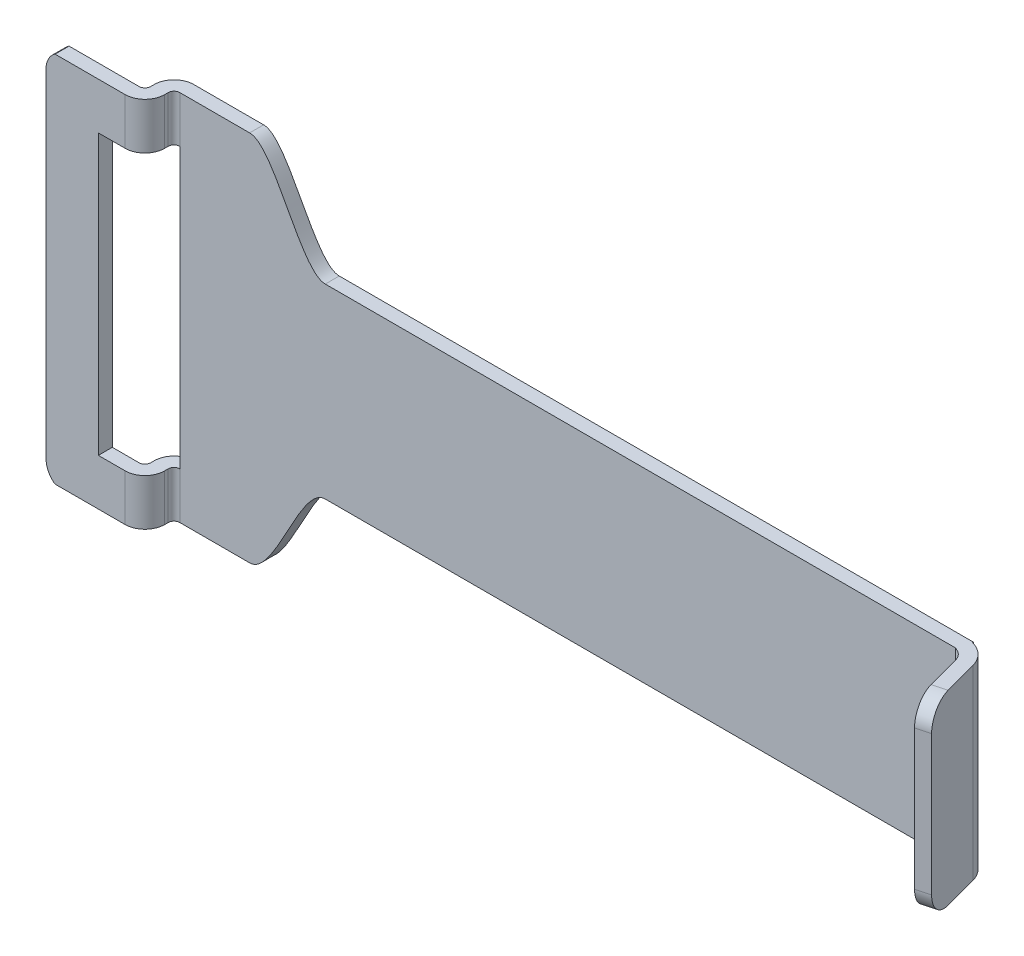
SolidWorks part; units mm, degrees
ref_plane "前视基准面" through (0, 0, 0) normal (0, 0, 1) x (1, 0, 0)
ref_plane "上视基准面" through (0, 0, 0) normal (0, 1, 0) x (1, 0, 0)
ref_plane "右视基准面" through (0, 0, 0) normal (1, 0, 0) x (0, 0, -1)
other "Configuration Table"
ref_plane "平板轮廓_基准面" through (0, 0, -306.8) normal (0, 0, 1) x (1, 0, 0)
sketch "草图_平板外形_总宽32_舌宽16_对称过渡" plane through (0, 0, -306.8) normal (0, 0, 1) x (1, 0, 0)
  line L0 (-3.5, 122.5) -> (2.5, 122.5)
  line L1 (9, 130.5) -> (63.2, 130.5)
  line L2 (63.2, 130.5) -> (63.2, 146.5)
  line L3 (63.2, 146.5) -> (9, 146.5)
  line L4 (2.5, 154.5) -> (-3.5, 154.5)
  line L5 (-3.5, 154.5) -> (-3.5, 122.5)
  spline S0 degree 3 poles (2.5, 122.5) (2.5683, 122.5047) (2.7079, 122.5143) (2.9138, 122.5869) (3.118, 122.6966) (3.3211, 122.845) (3.5237, 123.0274) (3.726, 123.2416) (3.9283, 123.4847) (4.1305, 123.7538) (4.3329, 124.0462) (4.5352, 124.3588) (4.7376, 124.689) (4.94, 125.0337) (5.1425, 125.3901) (5.345, 125.7552) (5.5475, 126.1261) (5.75, 126.5) (5.9525, 126.8739) (6.155, 127.2448) (6.3575, 127.6099) (6.56, 127.9663) (6.7624, 128.311) (6.9648, 128.6412) (7.1671, 128.9538) (7.3695, 129.2462) (7.5717, 129.5153) (7.774, 129.7584) (7.9763, 129.9726) (8.1789, 130.155) (8.382, 130.3034) (8.5862, 130.4131) (8.7921, 130.4857) (8.9317, 130.4953) (9, 130.5) knots 0 0 0 0 0.01923 0.039348 0.060985 0.084517 0.110121 0.137834 0.167605 0.199318 0.232816 0.267917 0.304415 0.342095 0.380729 0.420083 0.459921 0.5 0.540079 0.579917 0.619271 0.657905 0.695585 0.732083 0.767184 0.800682 0.832395 0.862166 0.889879 0.915483 0.939015 0.960652 0.98077 1 1 1 1
  spline S1 degree 3 poles (2.5, 154.5) (2.5683, 154.4953) (2.7079, 154.4857) (2.9138, 154.4131) (3.118, 154.3034) (3.3211, 154.155) (3.5237, 153.9726) (3.726, 153.7584) (3.9283, 153.5153) (4.1305, 153.2462) (4.3329, 152.9538) (4.5352, 152.6412) (4.7376, 152.311) (4.94, 151.9663) (5.1425, 151.6099) (5.345, 151.2448) (5.5475, 150.8739) (5.75, 150.5) (5.9525, 150.1261) (6.155, 149.7552) (6.3575, 149.3901) (6.56, 149.0337) (6.7624, 148.689) (6.9648, 148.3588) (7.1671, 148.0462) (7.3695, 147.7538) (7.5717, 147.4847) (7.774, 147.2416) (7.9763, 147.0274) (8.1789, 146.845) (8.382, 146.6966) (8.5862, 146.5869) (8.7921, 146.5143) (8.9317, 146.5047) (9, 146.5) knots 0 0 0 0 0.01923 0.039348 0.060985 0.084517 0.110121 0.137834 0.167605 0.199318 0.232816 0.267917 0.304415 0.342095 0.380729 0.420083 0.459921 0.5 0.540079 0.579917 0.619271 0.657905 0.695585 0.732083 0.767184 0.800682 0.832395 0.862166 0.889879 0.915483 0.939015 0.960652 0.98077 1 1 1 1
extrude "拉伸_板厚1点2" add sketch "草图_平板外形_总宽32_舌宽16_对称过渡" along normal blind 1.2
ref_plane "右端折弯截面_基准面" through (0, 130.5, 0) normal (0, 1, 0) x (1, 0, 0)
sketch "草图_右端折弯截面" plane through (0, 130.5, 0) normal (0, 1, 0) x (1, 0, 0)
  line L0 (9, 306.8) -> (63.5, 306.8)
  line L1 (63.5, 306.7238) -> (63.5, 306.8)
  line L2 (66.5123, 300.1915) -> (65.2182, 305.0212)
  line L3 (65.3532, 299.881) -> (66.5123, 300.1915)
  line L4 (64.0591, 304.7106) -> (65.3532, 299.881)
  line L5 (63.2, 305.6) -> (63.2, 305.5619)
  line L6 (9, 305.6) -> (63.2, 305.6)
  line L7 (9, 305.6) -> (9, 306.8)
  arc A0 (65.2182, 305.0212) -> (63.5, 306.7238) centre (62.9, 304.4) ccw
  arc A1 (63.2, 305.5619) -> (64.0591, 304.7106) centre (62.9, 304.4) cw
extrude "拉伸_舌宽16" add sketch "草图_右端折弯截面" along normal blind 16
ref_plane "左端错台截面_基准面" through (0, 122.5, 0) normal (0, 1, 0) x (1, 0, 0)
sketch "草图_左端错台截面" plane through (0, 122.5, 0) normal (0, 1, 0) x (1, 0, 0)
  line L0 (-5.7, 304.3) -> (-11.7194, 304.3)
  line L1 (-5.2, 305.1) -> (-5.2, 304.8)
  line L2 (-3.5, 306.8) -> (2.5, 306.8)
  line L3 (2.5, 305.6) -> (2.5, 306.8)
  line L4 (-3.5, 305.6) -> (2.5, 305.6)
  line L5 (-4, 304.8) -> (-4, 305.1)
  line L6 (-11.7194, 303.1) -> (-5.7, 303.1)
  line L7 (-11.7194, 304.3) -> (-11.7194, 303.1)
  arc A0 (-5.2, 304.8) -> (-5.7, 304.3) centre (-5.7, 304.8) cw
  arc A1 (-3.5, 306.8) -> (-5.2, 305.1) centre (-3.5, 305.1) ccw
  arc A2 (-4, 305.1) -> (-3.5, 305.6) centre (-3.5, 305.1) cw
  arc A3 (-5.7, 303.1) -> (-4, 304.8) centre (-5.7, 304.8) ccw
extrude "拉伸_头部总宽32" add sketch "草图_左端错台截面" along normal blind 32
ref_plane "榫槽_基准面" through (0, 0, -299) normal (0, 0, 1) x (1, 0, 0)
sketch "草图_榫槽净宽24_中线138点5" plane through (0, 0, -299) normal (0, 0, 1) x (1, 0, 0)
  line L0 (-3.5, 154.5) -> (-3.5, 122.5) construction
  line L1 (-8, 126.5) -> (-3.5, 126.5)
  line L2 (-8, 126.5) -> (-8, 150.5)
  line L3 (-8, 150.5) -> (-3.5, 150.5)
  line L4 (-3.5, 126.5) -> (-3.5, 150.5)
extrude "切除_榫槽24" cut sketch "草图_榫槽净宽24_中线138点5" against normal blind 20
ref_plane "头部完整外形_基准面" through (0, 0, -304.3) normal (0, 0, 1) x (1, 0, 0)
sketch "草图_头部完整外形_总宽32_槽24" plane through (0, 0, -304.3) normal (0, 0, 1) x (1, 0, 0)
  line L0 (-5.7, 154.5) -> (-5.7, 150.5)
  line L1 (-5.7, 150.5) -> (-8, 150.5)
  line L2 (-8, 150.5) -> (-8, 126.5)
  line L3 (-8, 126.5) -> (-5.7, 126.5)
  line L4 (-5.7, 126.5) -> (-5.7, 122.5)
  line L5 (-5.7, 122.5) -> (-11.7194, 122.5)
  line L6 (-12.5, 152.9654) -> (-12.5, 124.0346)
  line L7 (-5.7, 154.5) -> (-11.7194, 154.5)
  spline S0 degree 3 poles (-12.5, 124.0346) (-12.4999, 124.023) (-12.4998, 124) (-12.4989, 123.9654) (-12.4974, 123.9308) (-12.4954, 123.8962) (-12.4927, 123.8617) (-12.4895, 123.8271) (-12.4857, 123.7926) (-12.4812, 123.7581) (-12.4762, 123.7237) (-12.4706, 123.6893) (-12.4643, 123.655) (-12.4575, 123.6207) (-12.45, 123.5864) (-12.4419, 123.5522) (-12.4332, 123.5181) (-12.4239, 123.4841) (-12.4139, 123.4501) (-12.4032, 123.4163) (-12.392, 123.3825) (-12.38, 123.3488) (-12.3674, 123.3153) (-12.3541, 123.2818) (-12.3401, 123.2485) (-12.3254, 123.2153) (-12.31, 123.1823) (-12.2938, 123.1494) (-12.2769, 123.1167) (-12.2593, 123.0841) (-12.2409, 123.0518) (-12.2217, 123.0196) (-12.2017, 122.9877) (-12.1809, 122.956) (-12.1593, 122.9245) (-12.1368, 122.8933) (-12.1134, 122.8624) (-12.0892, 122.8319) (-12.064, 122.8016) (-12.0379, 122.7717) (-12.0108, 122.7422) (-11.9827, 122.7131) (-11.9536, 122.6844) (-11.9235, 122.6562) (-11.8923, 122.6286) (-11.86, 122.6015) (-11.8266, 122.575) (-11.792, 122.5492) (-11.7564, 122.524) (-11.7318, 122.508) (-11.7194, 122.5) knots 0 0 0 0 0.01928 0.038563 0.057853 0.077152 0.096463 0.11579 0.135135 0.154502 0.173895 0.193316 0.21277 0.232258 0.251786 0.271356 0.290973 0.31064 0.330361 0.350141 0.369982 0.389891 0.409871 0.429928 0.450065 0.470288 0.490604 0.511016 0.531531 0.552155 0.572894 0.593755 0.614746 0.635873 0.657144 0.678567 0.700151 0.721905 0.743837 0.765959 0.788279 0.810809 0.83356 0.856544 0.879771 0.903255 0.927007 0.951041 0.975367 1 1 1 1
  spline S1 degree 3 poles (-11.7194, 154.5) (-11.7318, 154.492) (-11.7564, 154.476) (-11.792, 154.4508) (-11.8266, 154.425) (-11.86, 154.3985) (-11.8923, 154.3714) (-11.9235, 154.3438) (-11.9536, 154.3156) (-11.9827, 154.2869) (-12.0108, 154.2578) (-12.0379, 154.2283) (-12.064, 154.1984) (-12.0892, 154.1681) (-12.1134, 154.1376) (-12.1368, 154.1067) (-12.1593, 154.0755) (-12.1809, 154.044) (-12.2017, 154.0123) (-12.2217, 153.9804) (-12.2409, 153.9482) (-12.2593, 153.9159) (-12.2769, 153.8833) (-12.2938, 153.8506) (-12.31, 153.8177) (-12.3254, 153.7847) (-12.3401, 153.7515) (-12.3541, 153.7182) (-12.3674, 153.6847) (-12.38, 153.6512) (-12.392, 153.6175) (-12.4032, 153.5837) (-12.4139, 153.5499) (-12.4239, 153.5159) (-12.4332, 153.4819) (-12.4419, 153.4478) (-12.45, 153.4136) (-12.4575, 153.3793) (-12.4643, 153.345) (-12.4706, 153.3107) (-12.4762, 153.2763) (-12.4812, 153.2419) (-12.4857, 153.2074) (-12.4895, 153.1729) (-12.4927, 153.1383) (-12.4954, 153.1038) (-12.4974, 153.0692) (-12.4989, 153.0346) (-12.4998, 153) (-12.4999, 152.977) (-12.5, 152.9654) knots 0 0 0 0 0.024633 0.048959 0.072993 0.096745 0.120229 0.143456 0.16644 0.189191 0.211721 0.234041 0.256163 0.278095 0.299849 0.321433 0.342856 0.364127 0.385254 0.406245 0.427106 0.447845 0.468469 0.488984 0.509396 0.529712 0.549935 0.570072 0.590129 0.610109 0.630018 0.649859 0.669639 0.68936 0.709027 0.728644 0.748214 0.767742 0.78723 0.806684 0.826105 0.845498 0.864865 0.88421 0.903537 0.922848 0.942147 0.961437 0.98072 1 1 1 1
extrude "拉伸_头部实体补全" add sketch "草图_头部完整外形_总宽32_槽24" along normal blind 1.2
ref_plane "两固定孔_基准面" through (0, 0, -305.6) normal (0, 0, 1) x (1, 0, 0)
sketch "草图_两固定孔_孔径可编辑" plane through (0, 0, -305.6) normal (0, 0, 1) x (1, 0, 0)
  circle A0 centre (18, 138.5) radius 1.1
  circle A1 centre (47, 138.5) radius 1.1
  dimension "D1" = 2.2
  dimension "D2" = 2.2
extrude "原铆接两孔_焊接版抑制_恢复可改回铆接" [suppressed] cut sketch "草图_两固定孔_孔径可编辑" against normal blind 20
fillet "圆角_舌片上下端角_R2" radius 2 2 edges at (65.9328, 130.5, -300.0362) (65.9328, 146.5, -300.0362)
ref_plane "基准面_点焊定位_非加工孔" through (0, 0, -305.6) normal (0, 0, 1) x (1, 0, 0)
sketch "草图_点焊定位_每片2点_X18和47_Y138点5_非加工孔" plane through (0, 0, -305.6) normal (0, 0, 1) x (1, 0, 0)
  line L0 (16, 138.5) -> (20, 138.5) construction
  line L1 (18, 136.5) -> (18, 140.5) construction
  line L2 (45, 138.5) -> (49, 138.5) construction
  line L3 (47, 136.5) -> (47, 140.5) construction
  point P0 (18, 138.5)
  point P5 (47, 138.5)
